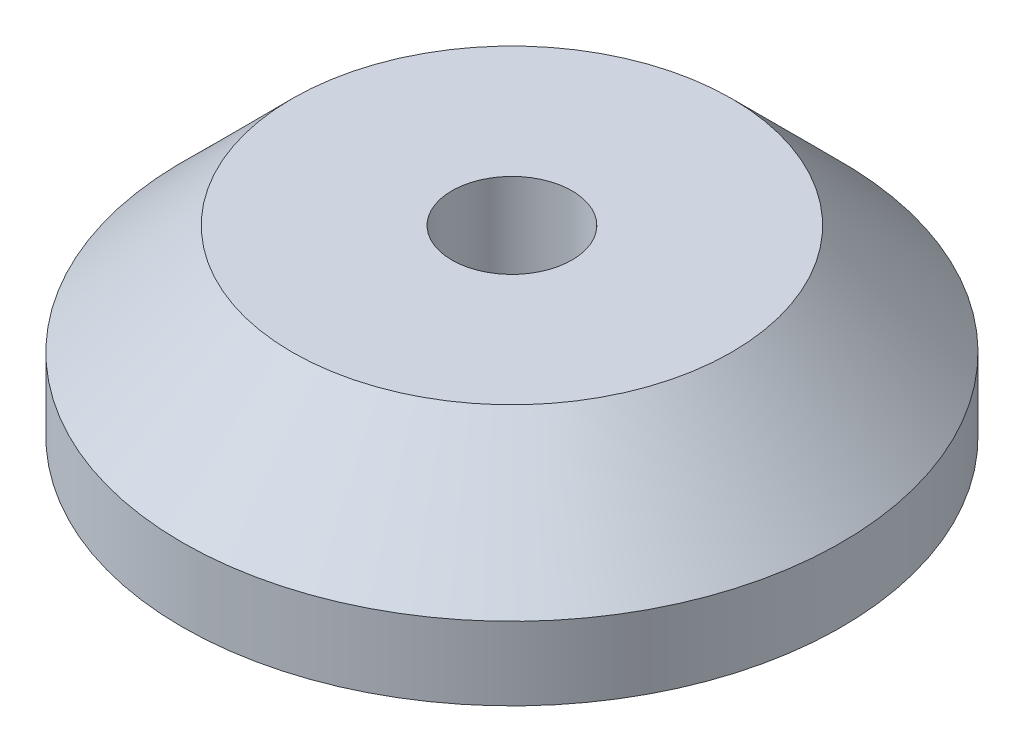
SolidWorks part; units mm, degrees
ref_plane "Front Plane" through (0, 0, 0) normal (0, 0, 1) x (1, 0, 0)
ref_plane "Top Plane" through (0, 0, 0) normal (0, 1, 0) x (1, 0, 0)
ref_plane "Right Plane" through (0, 0, 0) normal (1, 0, 0) x (0, 0, -1)
sketch "Sketch2" plane through (0, 0, 0) normal (0, 1, 0) x (1, 0, 0)
  circle A0 centre (0, 0) radius 22.5
  dimension "D1" = 45
extrude "Boss-Extrude1" add sketch "Sketch2" along normal blind 5
sketch "Sketch3" plane through (0, 5, 0) normal (0, 1, 0) x (1, 0, 0)
  circle A0 centre (0, 0) radius 22.5
  circle A1 centre (0, 0) radius 22.5 construction
extrude "Boss-Extrude2" add sketch "Sketch3" along normal blind 7.5 draft 45 separate body
sketch "Sketch4" plane through (0, 12.5, 0) normal (0, 1, 0) x (1, 0, 0)
  circle A0 centre (0, 0) radius 4.1
  dimension "D1" = 8.2
extrude "Cut-Extrude1" cut sketch "Sketch4" against normal through all
